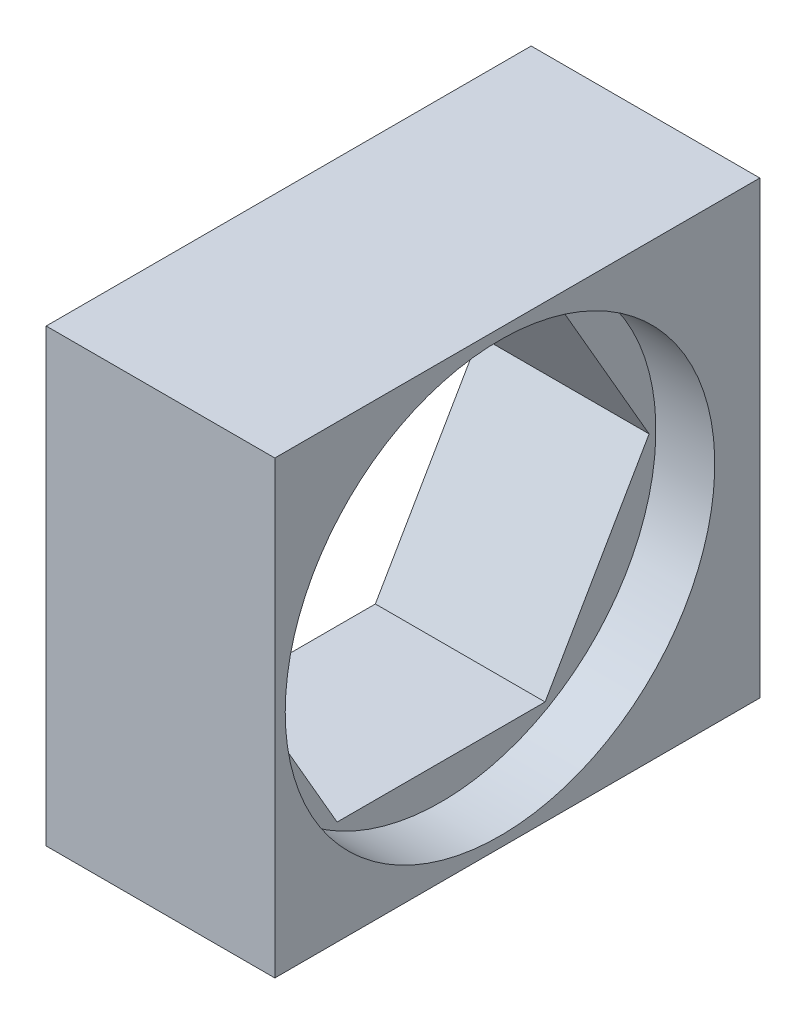
SolidWorks part; units mm, degrees
other "Preload Nut Anti Rotation Clip"
ref_plane "Front Plane" through (0, 0, 0) normal (0, 0, 1) x (1, 0, 0)
ref_plane "Top Plane" through (0, 0, 0) normal (0, 1, 0) x (1, 0, 0)
ref_plane "Right Plane" through (0, 0, 0) normal (1, 0, 0) x (0, 0, -1)
sketch3d "Nut clip blank sketch datum points"
  point P0 (41.1083, -35.5, -27)
  point P1 (51.1083, -35.5, -27)
  point P2 (41.1083, -25.5, -27)
ref_plane "Nut clip blank sketch plane" through (0, 0, -27) normal (0, 0, 1) x (1, 0, 0)
sketch "Nut clip blank sketch" plane through (0, 0, -27) normal (0, 0, 1) x (1, 0, 0)
  line L0 (41.1083, -35.5) -> (47.7083, -35.5)
  line L1 (47.7083, -35.5) -> (47.7083, -22.5)
  line L2 (47.7083, -22.5) -> (41.1083, -22.5)
  line L3 (41.1083, -22.5) -> (41.1083, -35.5)
extrude "Nut clip blank" add sketch "Nut clip blank sketch" along normal blind 14 separate body
sketch3d "M6 nut clearance sketch datum points"
  point P0 (41.0083, -29, -19.5)
  point P1 (41.0083, -19, -19.5)
  point P2 (41.0083, -29, -9.5)
ref_plane "M6 nut clearance sketch plane" through (41.0083, 0, 0) normal (1, 0, 0) x (0, 0, -1)
sketch "M6 nut clearance sketch" plane through (41.0083, 0, 0) normal (1, 0, 0) x (0, 0, -1)
  line L0 (16.4978, -23.8) -> (13.4956, -29)
  line L1 (13.4956, -29) -> (16.4978, -34.2)
  line L2 (16.4978, -34.2) -> (22.5022, -34.2)
  line L3 (22.5022, -34.2) -> (25.5044, -29)
  line L4 (25.5044, -29) -> (22.5022, -23.8)
  line L5 (22.5022, -23.8) -> (16.4978, -23.8)
  circle A0 centre (19.5, -29) radius 6.0044 construction
extrude "M6 nut clearance" cut sketch "M6 nut clearance sketch" along normal blind 5.3
sketch3d "Load washer relief sketch datum points"
  point P0 (46.0083, -29, -19.5)
  point P1 (46.0083, -19, -19.5)
  point P2 (46.0083, -29, -9.5)
ref_plane "Load washer relief sketch plane" through (46.0083, 0, 0) normal (1, 0, 0) x (0, 0, -1)
sketch "Load washer relief sketch" plane through (46.0083, 0, 0) normal (1, 0, 0) x (0, 0, -1)
  circle A0 centre (19.5, -29) radius 6.2
extrude "Load washer relief" cut sketch "Load washer relief sketch" along normal blind 1.9
